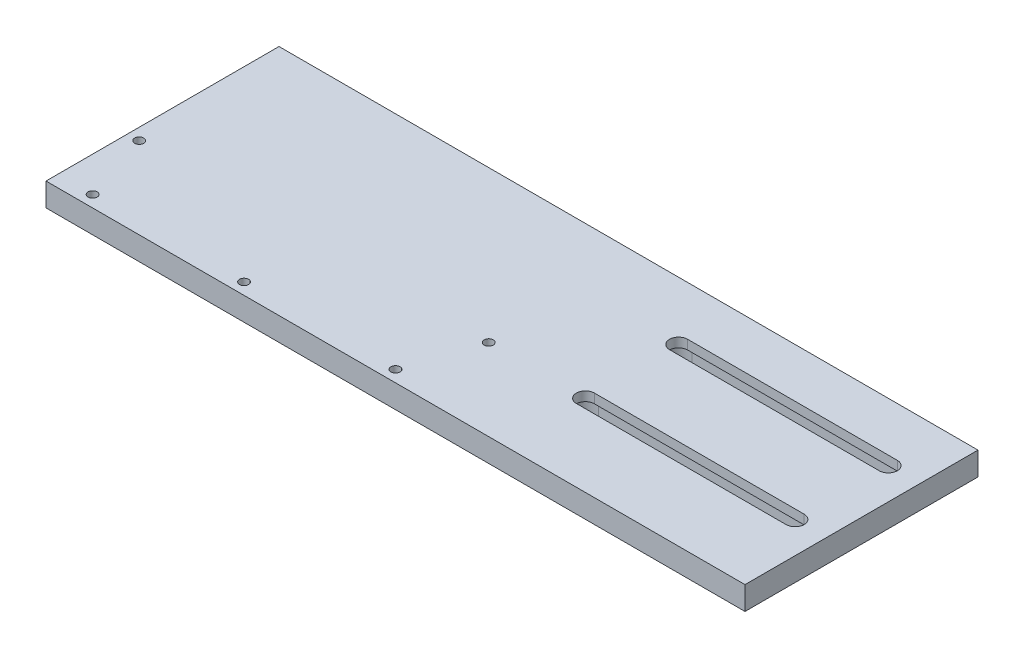
SolidWorks part; units mm, degrees
ref_plane "Front Plane" through (0, 0, 0) normal (0, 0, 1) x (1, 0, 0)
ref_plane "Top Plane" through (0, 0, 0) normal (0, 1, 0) x (1, 0, 0)
ref_plane "Right Plane" through (0, 0, 0) normal (1, 0, 0) x (0, 0, -1)
sketch "Sketch2" plane through (0, 0, 0) normal (0, 1, 0) x (1, 0, 0)
  line L1 (-190.5, -63.5) -> (190.5, -63.5)
  line L2 (-190.5, -63.5) -> (-190.5, 63.5)
  line L3 (-190.5, 63.5) -> (190.5, 63.5)
  line L4 (190.5, -63.5) -> (190.5, 63.5)
  line L5 (-190.5, -63.5) -> (190.5, 63.5) construction
  line L6 (-190.5, 63.5) -> (190.5, -63.5) construction
  point P0 (0, 0)
  dimension "D1" = 381
  dimension "D2" = 127
extrude "Boss-Extrude1" add sketch "Sketch2" along normal blind 12.7
sketch "Sketch8" plane through (0, 0, 0) normal (0, -1, 0) x (1, 0, 0)
  line L0 (59.055, 23.9776) -> (173.355, 23.9776)
  line L1 (59.055, 14.1224) -> (173.355, 14.1224)
  line L2 (59.055, -26.8224) -> (173.355, -26.8224)
  line L3 (-190.5, -63.5) -> (-190.5, 63.5) construction
  line L4 (173.355, -36.6776) -> (59.055, -36.6776)
  line L5 (-190.5, 63.5) -> (190.5, 63.5) construction
  arc A0 (59.055, 23.9776) -> (59.055, 14.1224) centre (59.055, 19.05) ccw
  arc A1 (173.355, 14.1224) -> (173.355, 23.9776) centre (173.355, 19.05) ccw
  arc A2 (59.055, -26.8224) -> (59.055, -36.6776) centre (59.055, -31.75) ccw
  arc A3 (173.355, -36.6776) -> (173.355, -26.8224) centre (173.355, -31.75) ccw
  dimension "D1" = 114.3
  dimension "D3" = 4.9276
  dimension "D6" = 4.9276
  dimension "D2" = 114.3
  dimension "D4" = 249.555
  dimension "D5" = 249.555
  dimension "D7" = 44.45
  dimension "D8" = 50.8
extrude "Cut-Extrude1" cut sketch "Sketch8" against normal blind 12.7
hole_wizard "CSK for #10 Flat Head Machine Screw (100)1" positions "Sketch12" profile "Sketch11" countersink size "#10" standard "ANSI Inch" end condition through all
sketch "Sketch12" plane through (0, 0, 0) normal (0, -1, 0) x (-1, 0, 0)
  line L0 (190.5, 63.5) -> (190.5, -63.5) construction
  line L1 (190.5, -63.5) -> (-190.5, -63.5) construction
  point P0 (171.45, -57.15)
  point P2 (88.9, -57.15)
  point P4 (6.35, -57.15)
  dimension "D1" = 19.05
  dimension "D2" = 101.6
  dimension "D3" = 184.15
  dimension "D4" = 6.35
  dimension "D5" = 6.35
  dimension "D6" = 6.35
sketch "Sketch11" plane through (-171.45, 0, 57.15) normal (1, 0, 0) x (0, 0, -1)
  line L0 (0, 0) -> (0, 12.7)
  line L1 (0, 12.7) -> (2.4892, 12.7)
  line L2 (2.4892, 12.7) -> (2.4892, 2.0141)
  line L3 (2.4892, 2.0141) -> (4.8895, 0)
  line L5 (4.8895, 0) -> (0, 0)
  line L6 (-2.4892, 2.0141) -> (-4.8895, 0) construction
  line L11 (0, -6.35) -> (0, 107.95) construction
  dimension "Thru Hole Dia." = 4.9784
  dimension "Thru Hole Depth" = 12.7
  dimension "Near C'Sink Dia." = 9.779
  dimension "Near C'Sink Angle" = 100
hole_wizard "CSK for #10 Flat Head Machine Screw (100)2" positions "Sketch14" profile "Sketch13" countersink size "#10" standard "ANSI Inch" end condition through all
sketch "Sketch14" plane through (0, 0, 0) normal (0, -1, 0) x (-1, 0, 0)
  line L0 (190.5, -63.5) -> (-190.5, -63.5) construction
  line L1 (190.5, 63.5) -> (190.5, -63.5) construction
  point P0 (184.15, -19.05)
  point P2 (-6.35, -19.05)
  dimension "D1" = 44.45
  dimension "D2" = 44.45
  dimension "D3" = 6.35
  dimension "D4" = 190.5
sketch "Sketch13" plane through (-184.15, 0, 19.05) normal (1, 0, 0) x (0, 0, -1)
  line L0 (0, 0) -> (0, 12.7)
  line L1 (0, 12.7) -> (2.4892, 12.7)
  line L2 (2.4892, 12.7) -> (2.4892, 2.0141)
  line L3 (2.4892, 2.0141) -> (4.8895, 0)
  line L5 (4.8895, 0) -> (0, 0)
  line L6 (-2.4892, 2.0141) -> (-4.8895, 0) construction
  line L11 (0, -6.35) -> (0, 107.95) construction
  dimension "Thru Hole Dia." = 4.9784
  dimension "Thru Hole Depth" = 12.7
  dimension "Near C'Sink Dia." = 9.779
  dimension "Near C'Sink Angle" = 100
sketch "Sketch16" plane through (0, 0, 0) normal (0, -1, 0) x (1, 0, 0)
  line L0 (59.055, 26.289) -> (173.355, 26.289)
  line L2 (173.355, 11.811) -> (59.055, 11.811)
  line L3 (59.055, -24.511) -> (173.355, -24.511)
  line L5 (173.355, -38.989) -> (59.055, -38.989)
  arc A0 (59.055, 26.289) -> (59.055, 11.811) centre (59.055, 19.05) ccw
  arc A1 (59.055, -24.511) -> (59.055, -38.989) centre (59.055, -31.75) ccw
  arc A2 (173.355, 11.811) -> (173.355, 26.289) centre (173.355, 19.05) ccw
  arc A3 (173.355, -38.989) -> (173.355, -24.511) centre (173.355, -31.75) ccw
extrude "Cut-Extrude3" cut sketch "Sketch16" against normal blind 7.62
